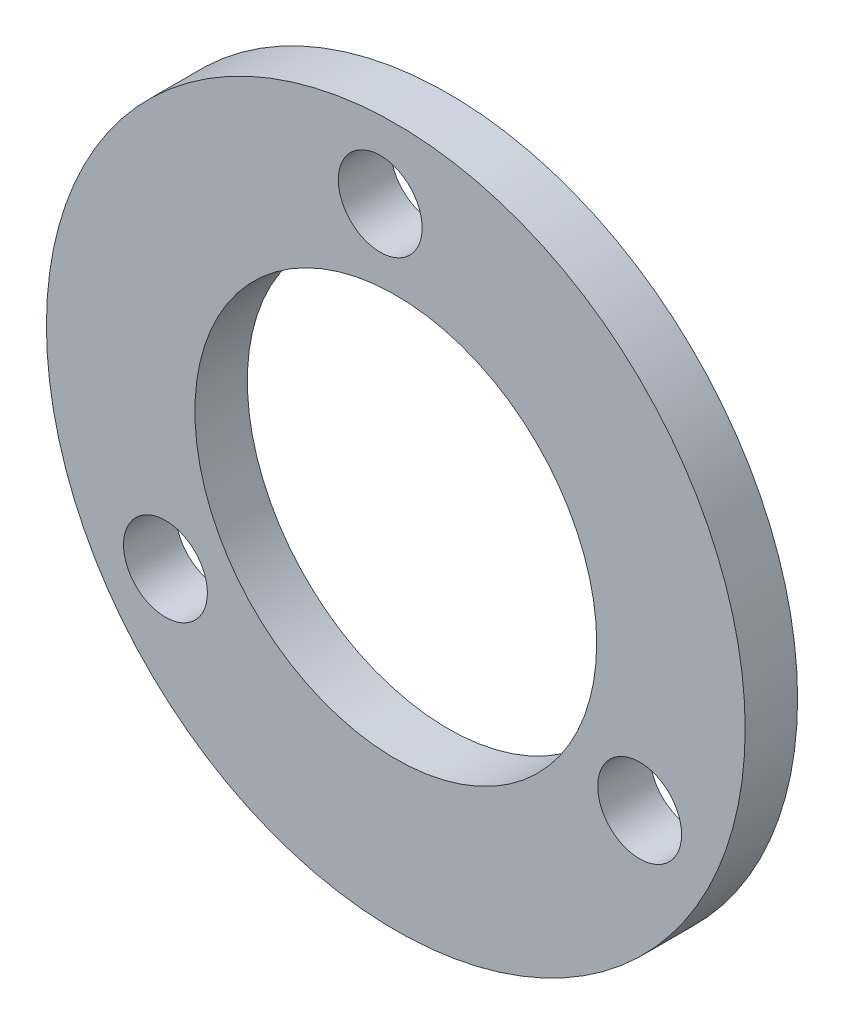
SolidWorks part; units mm, degrees
ref_plane "Front Plane" through (0, 0, 0) normal (0, 0, 1) x (1, 0, 0)
ref_plane "Top Plane" through (0, 0, 0) normal (0, 1, 0) x (1, 0, 0)
ref_plane "Right Plane" through (0, 0, 0) normal (1, 0, 0) x (0, 0, -1)
sketch "Sketch2" plane through (0, 0, 0) normal (0, 0, 1) x (1, 0, 0)
  circle A5 centre (-13.1848, -8.6603) radius 2.4
  circle A6 centre (13.9582, -7.0655) radius 2.4
  circle A7 centre (0, 0) radius 11.5
  circle A8 centre (0, 0) radius 20
  circle A9 centre (-0.8918, 15.5828) radius 2.4
  point P0 (-15.2103, -4.4885)
  dimension "D1" = 40
  dimension "D2" = 4.8
  dimension "D3" = 23
  dimension "D4" = 4.8
  dimension "D5" = 4.8
extrude "Boss-Extrude1" add sketch "Sketch2" along normal blind 3
